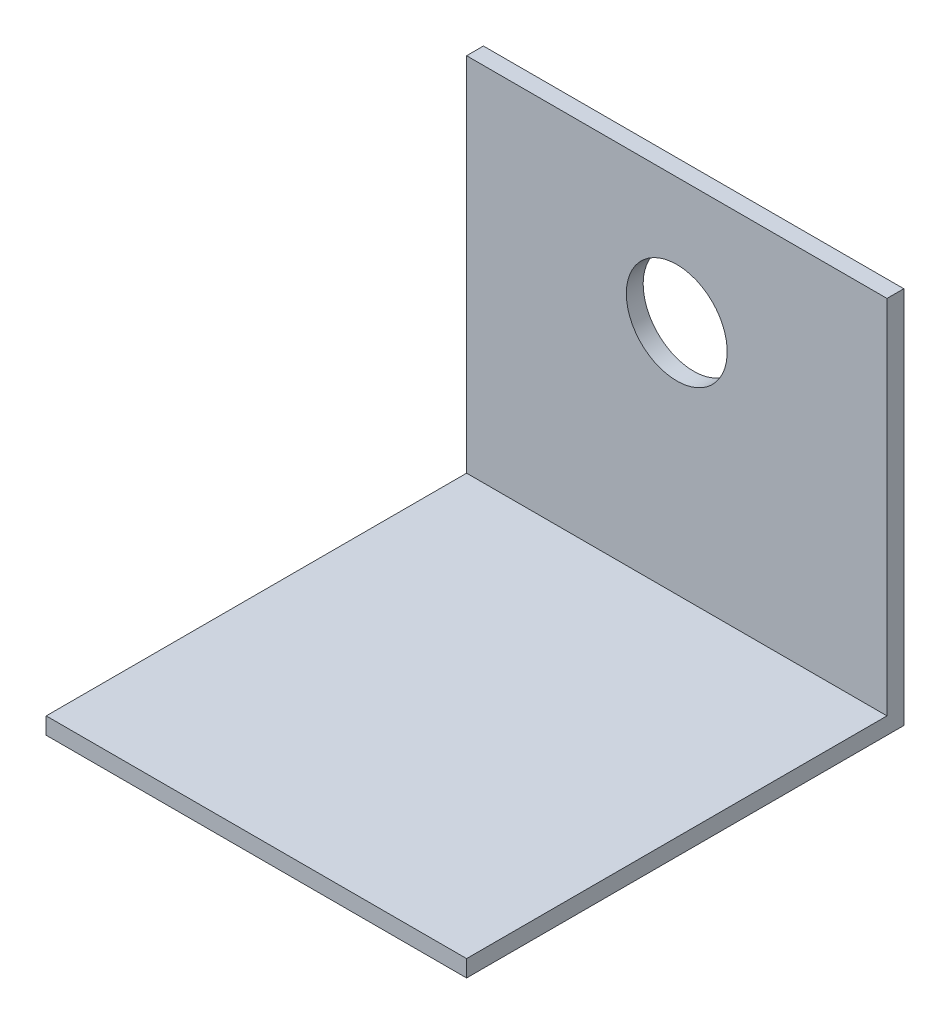
SolidWorks part; units mm, degrees
ref_plane "Front Plane" through (0, 0, 0) normal (0, 0, 1) x (1, 0, 0)
ref_plane "Top Plane" through (0, 0, 0) normal (0, 1, 0) x (1, 0, 0)
ref_plane "Right Plane" through (0, 0, 0) normal (1, 0, 0) x (0, 0, -1)
sketch "Sketch1" plane through (0, 0, 0) normal (0, 1, 0) x (1, 0, 0)
  line L1 (0, 0) -> (50, 0)
  line L2 (0, 0) -> (0, -50)
  line L3 (0, -50) -> (50, -50)
  line L4 (50, 0) -> (50, -50)
  dimension "D1" = 50
  dimension "D2" = 50
extrude "Boss-Extrude1" add sketch "Sketch1" along normal blind 2
sketch "Sketch2" plane through (0, 0, 0) normal (0, 0, -1) x (-1, 0, 0)
  line L0 (-25, 45) -> (-25, 0) construction
  line L1 (-50, 0) -> (0, 0)
  line L2 (-50, 0) -> (-50, 45)
  line L3 (-50, 45) -> (0, 45)
  line L4 (0, 0) -> (0, 45)
  circle A0 centre (-25, 30) radius 6
  dimension "D3" = 12
  dimension "D1" = 50
  dimension "D2" = 45
  dimension "D4" = 15
extrude "Boss-Extrude2" add sketch "Sketch2" along normal blind 2
